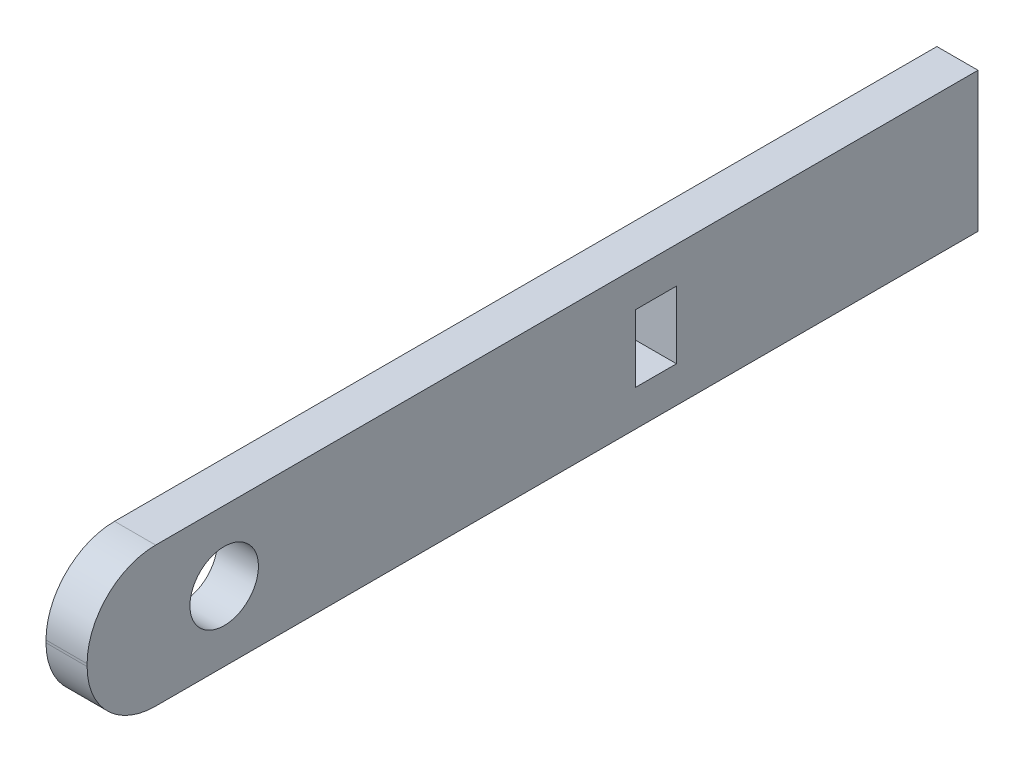
SolidWorks part; units mm, degrees
ref_plane "Front Plane" through (0, 0, 0) normal (0, 0, 1) x (1, 0, 0)
ref_plane "Top Plane" through (0, 0, 0) normal (0, 1, 0) x (1, 0, 0)
ref_plane "Right Plane" through (0, 0, 0) normal (1, 0, 0) x (0, 0, -1)
sketch "Sketch1" plane through (0, 0, 0) normal (1, 0, 0) x (0, 0, -1)
  line L1 (0, 0) -> (65, 0)
  line L2 (0, 0) -> (0, 10.18)
  line L3 (0, 10.18) -> (65, 10.18)
  line L4 (65, 0) -> (65, 10.18)
  dimension "D1" = 10.18
  dimension "D2" = 65
extrude "Boss-Extrude1" add sketch "Sketch1" along normal blind 3
hole_wizard "Ø5.0mm Dowel Hole1" positions "Sketch2" profile "Sketch3" hole size "Ø5.0" standard "ANSI Metric"
sketch "Sketch2" plane through (3, 0, 0) normal (1, 0, 0) x (0, 0, -1)
  line L0 (0, 0) -> (65, 0) construction
  line L1 (0, 10.18) -> (0, 0) construction
  point P0 (10, 5.09)
  dimension "D1" = 5.09
  dimension "D2" = 10
sketch "Sketch3" plane through (3, 5.09, -10) normal (0, 1, 0) x (0, 0, -1)
  line L0 (0, 0) -> (0, 4.5022)
  line L1 (0, 4.5022) -> (2.5, 3)
  line L2 (2.5, 3) -> (2.5, 0)
  line L5 (2.5, 0) -> (0, 0)
  line L10 (0, 4.5022) -> (-2.5, 3) construction
  line L11 (0, -6.35) -> (0, 107.95) construction
  dimension "Hole Dia." = 5
  dimension "Hole Depth" = 3
  dimension "Drill Angle" = 118
fillet "Fillet1" radius 5 2 edges at (1.5, 0, 0) (1.5, 10.18, 0)
sketch "Sketch4" plane through (3, 0, 0) normal (1, 0, 0) x (0, 0, -1)
  line L0 (0, 5.18) -> (0, 5) construction
  line L1 (40, 2.635) -> (43, 2.635)
  line L2 (40, 2.635) -> (40, 7.545)
  line L3 (40, 7.545) -> (43, 7.545)
  line L4 (43, 2.635) -> (43, 7.545)
  line L5 (5, 0) -> (65, 0) construction
  dimension "D1" = 3
  dimension "D2" = 4.91
  dimension "D3" = 2.635
  dimension "D4" = 40
extrude "Cut-Extrude1" cut sketch "Sketch4" against normal blind 3
equation "\"D1@Sketch2\"=\"D1@Sketch1\"/2"
equation "\"D2@Sketch4\"=\"D1@Sketch1\"/2-\"Kerf\""
equation "\"D3@Sketch4\"=(\"D1@Sketch1\"-\"D2@Sketch4\")/2"
equation "\"Kerf\"= 0.18"
